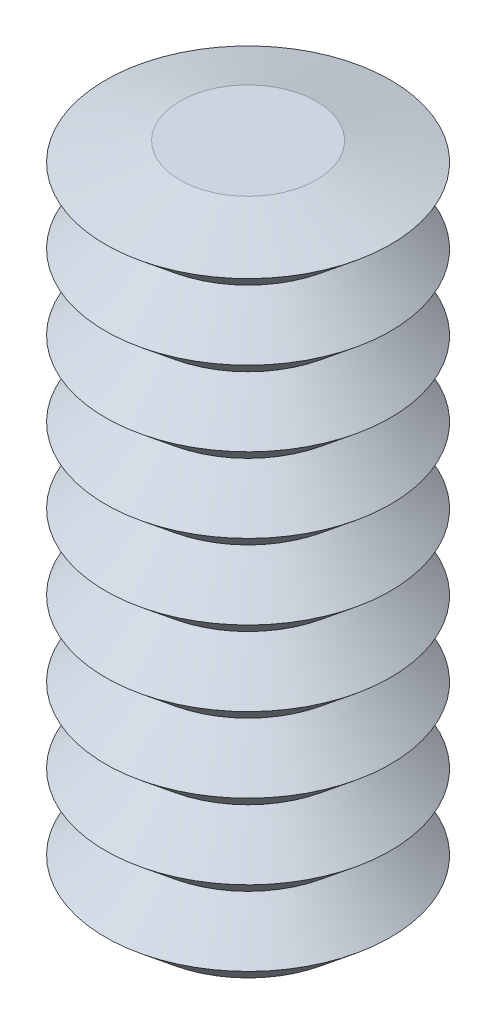
SolidWorks part; units mm, degrees
material "AISI 304"
ref_plane "Alzado" through (0, 0, 0) normal (0, 0, 1) x (1, 0, 0)
ref_plane "Planta" through (0, 0, 0) normal (0, 1, 0) x (1, 0, 0)
ref_plane "Vista lateral" through (0, 0, 0) normal (1, 0, 0) x (0, 0, -1)
sketch "Sketch1" plane through (0, 0, 0) normal (0, 0, 1) x (1, 0, 0)
  line L0 (0, 0) -> (1.82, 0)
  line L1 (1.82, 0) -> (3.8, -0.5)
  line L2 (3.8, -0.5) -> (2.6, -1.5)
  line L3 (2.6, -1.5) -> (3.8, -2.5)
  line L4 (3.8, -2.5) -> (2.6, -3.5)
  line L5 (2.6, -3.5) -> (3.8, -4.5)
  line L6 (3.8, -4.5) -> (2.6, -5.5)
  line L7 (2.6, -5.5) -> (3.8, -6.5)
  line L8 (3.8, -6.5) -> (2.6, -7.5)
  line L9 (2.6, -7.5) -> (3.8, -8.5)
  line L10 (3.8, -8.5) -> (2.6, -9.5)
  line L11 (2.6, -9.5) -> (3.8, -10.5)
  line L12 (3.8, -10.5) -> (2.6, -11.5)
  line L13 (2.6, -11.5) -> (3.8, -12.5)
  line L14 (3.8, -12.5) -> (2.6, -13.5)
  line L15 (2.6, -13.5) -> (3.8, -14.5)
  line L16 (3.8, -14.5) -> (2.6, -15.5)
  line L17 (2.6, -15.5) -> (3.8, -16.5)
  line L18 (3.8, -16.5) -> (2.6, -17.5)
  line L19 (2.6, -17.5) -> (1.82, -18)
  line L20 (1.82, -18) -> (0, -18)
  line L21 (0, -18) -> (0, 0)
  line L22 (0, -22) -> (0, 4) construction
revolve "Elemento_elastico_en_serie" add sketch "Sketch1" angle 360 about L22
